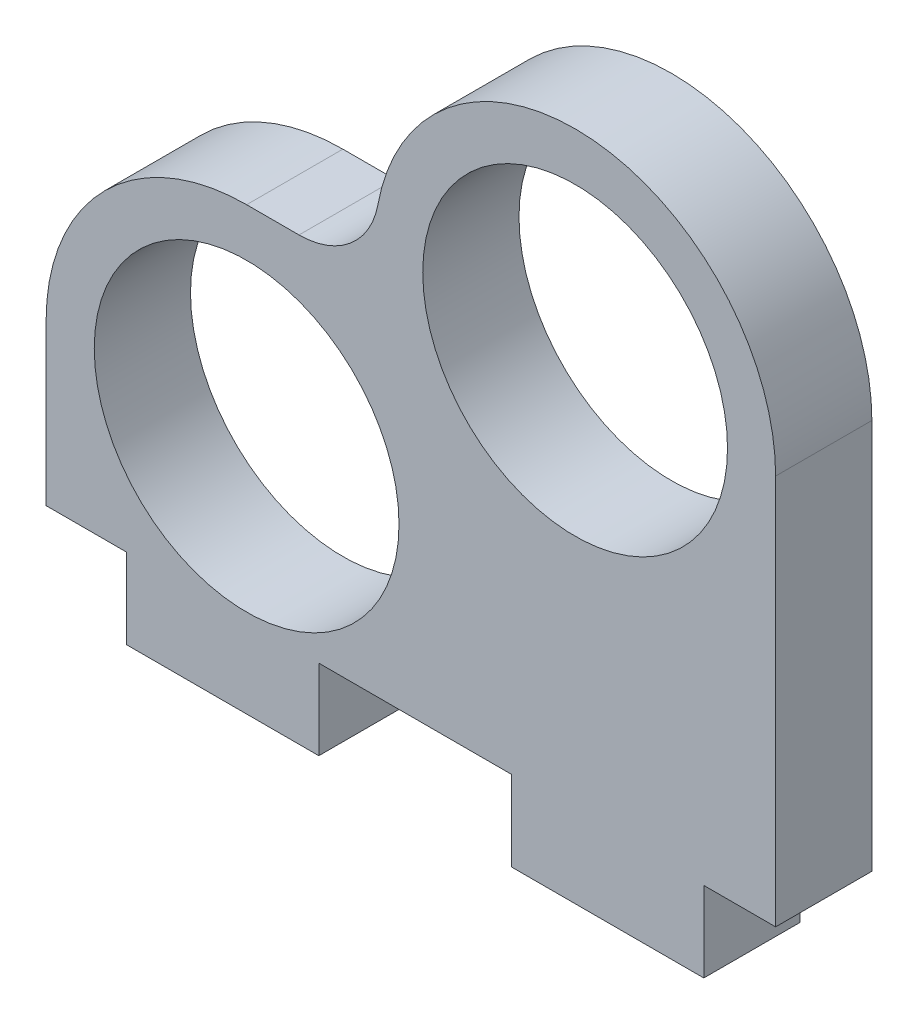
SolidWorks part; units mm, degrees
ref_plane "Alzado" through (0, 0, 0) normal (0, 0, 1) x (1, 0, 0)
ref_plane "Planta" through (0, 0, 0) normal (0, 1, 0) x (1, 0, 0)
ref_plane "Vista lateral" through (0, 0, 0) normal (1, 0, 0) x (0, 0, -1)
sketch "Croquis1" plane through (0, 0, 0) normal (0, 0, 1) x (1, 0, 0)
  line L0 (-12.5, 0) -> (-12.5, -10)
  line L1 (0, 0) -> (20.4788, 14.3394) construction
  line L2 (0, 12.5) -> (3.2666, 12.5)
  line L3 (-12.5, -10) -> (32.9788, -10) construction
  line L4 (32.9788, 14.3394) -> (32.9788, -10)
  line L5 (4.5, -15) -> (-7.5, -15)
  line L6 (28.5, -15) -> (16.5, -15)
  line L9 (-12.5, -10) -> (-7.5, -10)
  line L10 (-7.5, -15) -> (-7.5, -10)
  line L13 (32.9788, -10) -> (28.5, -10)
  line L14 (28.5, -15) -> (28.5, -10)
  line L16 (16.5, -15) -> (16.5, -10)
  line L17 (16.5, -10) -> (4.5, -10)
  line L18 (4.5, -15) -> (4.5, -10)
  arc A0 (0, 12.5) -> (-12.5, 0) centre (0, 0) ccw
  circle A1 centre (0, 0) radius 9.5
  arc A2 (32.9788, 14.3394) -> (8.1844, 16.597) centre (20.4788, 14.3394) ccw
  circle A3 centre (20.4788, 14.3394) radius 9.5
  arc A4 (3.2666, 12.5) -> (8.1844, 16.597) centre (3.2666, 17.5) ccw
  dimension "D1" = 19
  dimension "D2" = 25
  dimension "D4" = 19
  dimension "D5" = 25
  dimension "D8" = 5
  dimension "D3" = 25
  dimension "D6" = 10
  dimension "D7" = 35
  dimension "D9" = 5
  dimension "D10" = 5
  dimension "D11" = 12
  dimension "D12" = 12
  dimension "D13" = 12
extrude "Saliente-Extruir1" add sketch "Croquis1" along normal blind 6
